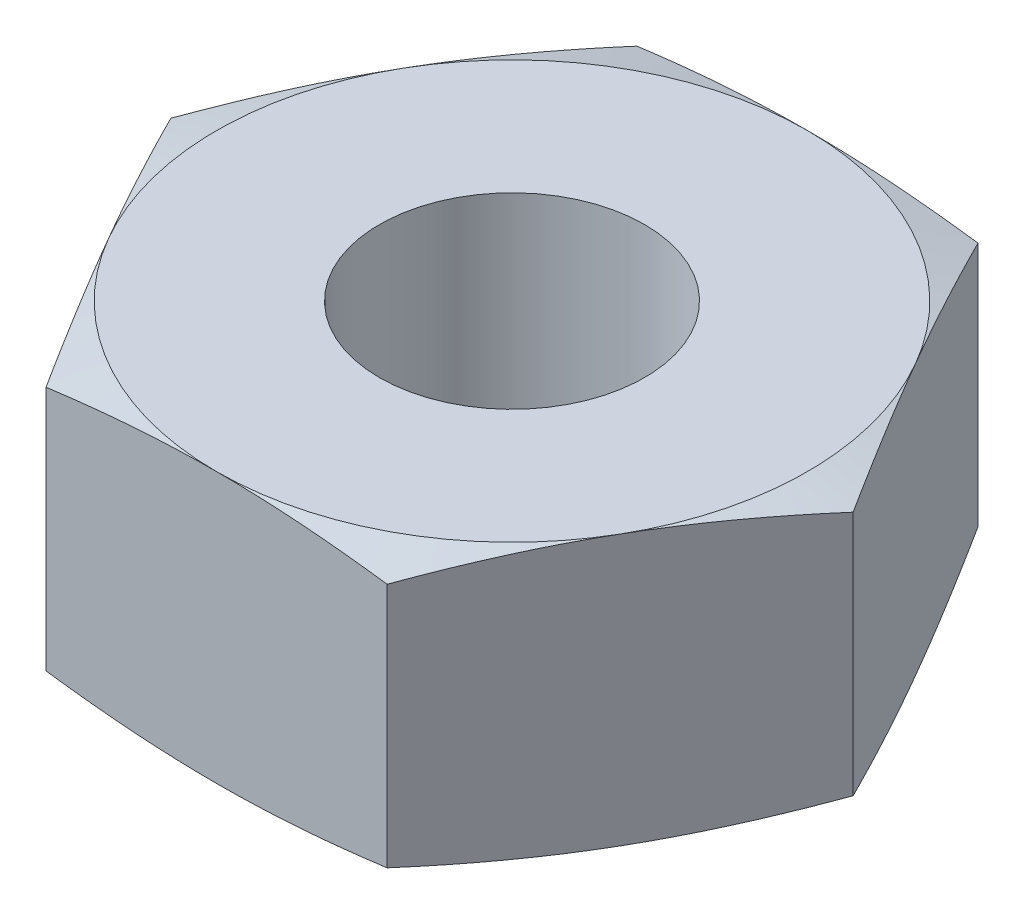
SolidWorks part; units mm, degrees
material "Plain Carbon Steel"
ref_plane "Front Plane" through (0, 0, 0) normal (0, 0, 1) x (1, 0, 0)
ref_plane "Top Plane" through (0, 0, 0) normal (0, 1, 0) x (1, 0, 0)
ref_plane "Right Plane" through (0, 0, 0) normal (1, 0, 0) x (0, 0, -1)
sketch "Sketch1" plane through (0, 0, 0) normal (0, 1, 0) x (1, 0, 0)
  line L1 (4.0415, 0) -> (2.0207, 3.5)
  line L2 (2.0207, 3.5) -> (-2.0207, 3.5)
  line L3 (-2.0207, 3.5) -> (-4.0415, 0)
  line L4 (-4.0415, 0) -> (-2.0207, -3.5)
  line L5 (-2.0207, -3.5) -> (2.0207, -3.5)
  line L6 (2.0207, -3.5) -> (4.0415, 0)
  circle A0 centre (0, 0) radius 3.5 construction
  dimension "D1" = 7
extrude "Extrude1" add sketch "Sketch1" along normal mid plane 3.2
sketch "Sketch2" plane through (0, 0, 0) normal (1, 0, 0) x (0, 0, -1)
  line L0 (-3.5, 1.6) -> (-77.9305, -18.3436)
  line L1 (-77.9305, -18.3436) -> (-77.9305, 1.6)
  line L2 (-77.9305, 1.6) -> (-3.5, 1.6)
  line L3 (0, 0) -> (0, 7.9376) construction
  dimension "D1" = 15
revolve "Cut-Revolve1" cut sketch "Sketch2" angle 360 about L3
mirror "Mirror1" about plane through (0, 0, 0) normal (0, 1, 0) of "Cut-Revolve1"
sketch "Sketch3" plane through (0, 1.6, 0) normal (0, 1, 0) x (1, 0, 0)
  circle A0 centre (0, 0) radius 1.571
  dimension "D1" = 3.142
extrude "Extrude2" cut sketch "Sketch3" against normal through all
cosmetic thread "Cosmetic Thread1" parameters "D2"=4
